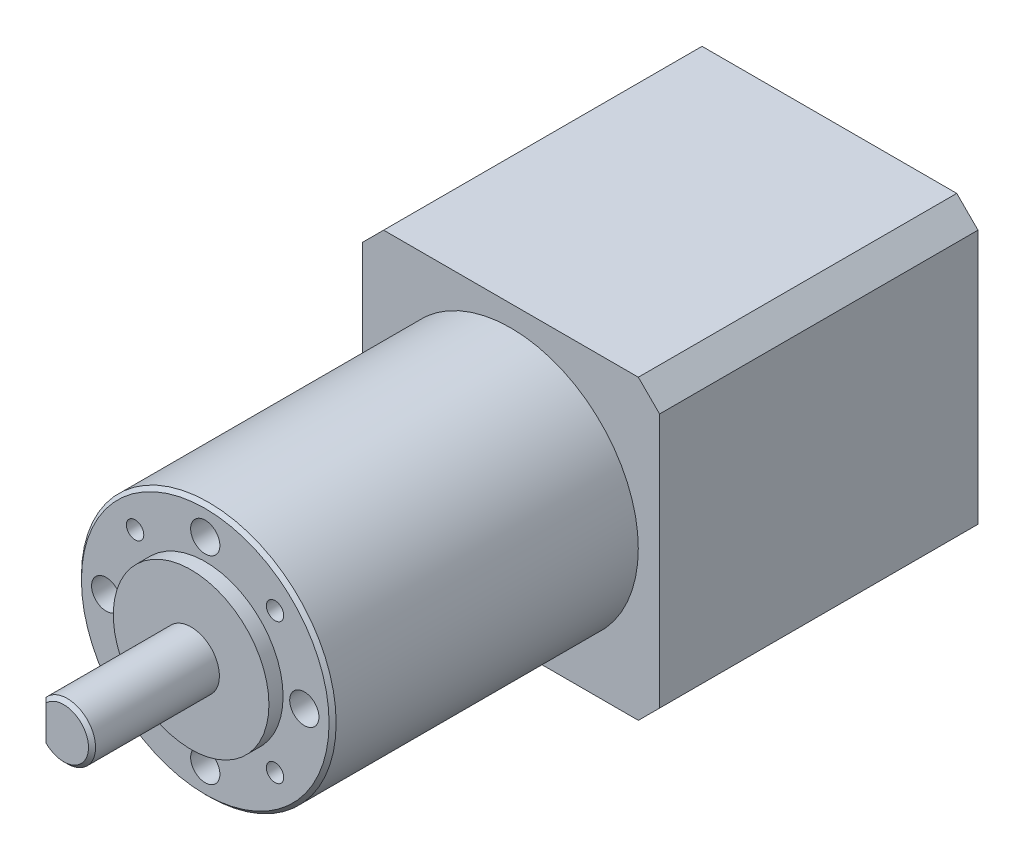
SolidWorks part; units mm, degrees
ref_plane "Front Plane" through (0, 0, 0) normal (0, 0, 1) x (1, 0, 0)
ref_plane "Top Plane" through (0, 0, 0) normal (0, 1, 0) x (1, 0, 0)
ref_plane "Right Plane" through (0, 0, 0) normal (1, 0, 0) x (0, 0, -1)
ref_plane "Plane1" through (0, 42, 0) normal (0, 1, 0) x (1, 0, 0)
sketch "Sketch1" plane through (0, 42, 0) normal (0, 1, 0) x (1, 0, 0)
  line L0 (42, 0) -> (0, 0)
  line L1 (0, 0) -> (0, -45)
  line L2 (0, -45) -> (42, -45)
  line L3 (42, -45) -> (42, 0)
extrude "Boss-Extrude1" add sketch "Sketch1" against normal blind 42
sketch "Sketch2" plane through (0, 0, 45) normal (0, 0, 1) x (1, 0, 0)
  circle A0 centre (20.9927, 21.0291) radius 18
extrude "Boss-Extrude2" add sketch "Sketch2" along normal blind 43.2
sketch "Sketch3" plane through (0, 0, 88.2) normal (0, 0, 1) x (1, 0, 0)
  circle A0 centre (20.9927, 21.0291) radius 11
extrude "Boss-Extrude3" add sketch "Sketch3" along normal blind 2
sketch "Sketch4" plane through (0, 0, 90.2) normal (0, 0, 1) x (1, 0, 0)
  circle A0 centre (20.9927, 21.0291) radius 4
extrude "Boss-Extrude4" add sketch "Sketch4" along normal blind 18
sketch "Sketch5" plane through (0, 0, 108.2) normal (0, 0, 1) x (1, 0, 0)
  line L0 (17.9875, 18.3892) -> (18.0045, 23.6881)
  arc A0 (18.0045, 23.6881) -> (17.9875, 18.3892) centre (20.9927, 21.0291) ccw
extrude "Cut-Extrude1" cut sketch "Sketch5" against normal blind 15
hole_wizard "M2 Clearance Hole1" positions "Sketch7" profile "Sketch6" hole size "M2" standard "ANSI Metric"
sketch "Sketch7" plane through (0, 0, 88.2) normal (0, 0, 1) x (1, 0, 0)
  point P0 (11.0758, 30.9626)
  point P1 (30.8575, 30.9626)
  point P2 (11.0758, 11.1431)
  point P3 (30.8575, 11.1431)
sketch "Sketch6" plane through (11.0758, 30.9626, 88.2) normal (1, 0, 0) x (0, -1, 0)
  line L0 (0, 0) -> (0, 4)
  line L1 (0, 4) -> (1.2295, 4)
  line L2 (1.2295, 4) -> (1.2295, 0)
  line L5 (1.2295, 0) -> (0, 0)
  line L10 (0, 4) -> (-1.2295, 4) construction
  line L11 (0, -6.35) -> (0, 107.95) construction
  dimension "Hole Dia." = 2.459
  dimension "Hole Depth" = 4
  dimension "Drill Angle" = 180
hole_wizard "M3.5 Clearance Hole1" positions "Sketch9" profile "Sketch8" hole size "M3.5" standard "ANSI Metric"
sketch "Sketch9" plane through (0, 0, 88.2) normal (0, 0, 1) x (1, 0, 0)
  point P0 (6.9927, 21.0291)
  point P1 (34.9927, 21.0291)
  point P2 (20.9927, 7.0291)
  point P3 (20.9927, 35.0291)
sketch "Sketch8" plane through (6.9927, 21.0291, 88.2) normal (1, 0, 0) x (0, -1, 0)
  line L0 (0, 0) -> (0, 5)
  line L1 (0, 5) -> (2.067, 5)
  line L2 (2.067, 5) -> (2.067, 0)
  line L5 (2.067, 0) -> (0, 0)
  line L10 (0, 5) -> (-2.067, 5) construction
  line L11 (0, -6.35) -> (0, 107.95) construction
  dimension "Hole Dia." = 4.134
  dimension "Hole Depth" = 5
  dimension "Drill Angle" = 180
chamfer "Chamfer1" distance 3 angle 45 4 edges at (42, 0, 22.5) (0, 0, 22.5) (42, 42, 22.5) (0, 42, 22.5)
chamfer "Chamfer2" distance 0.5 angle 45 3 edges at (24.9927, 21.0162, 108.2) (17.996, 21.0387, 108.2) (38.9927, 21.0291, 88.2)
